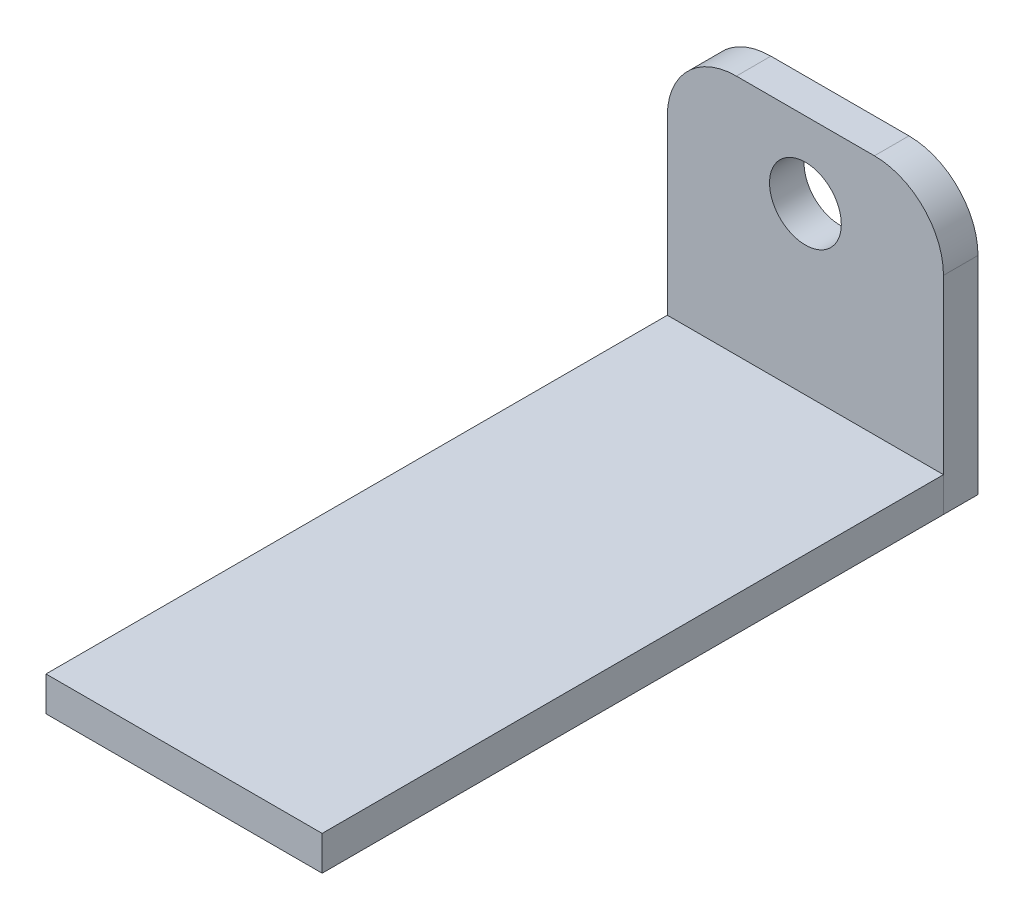
SolidWorks part; units mm, degrees
material "AISI 4130 Steel, annealed at 865C"
ref_plane "Front Plane" through (0, 0, 0) normal (0, 0, 1) x (1, 0, 0)
ref_plane "Top Plane" through (0, 0, 0) normal (0, 1, 0) x (1, 0, 0)
ref_plane "Right Plane" through (0, 0, 0) normal (1, 0, 0) x (0, 0, -1)
sketch "Sketch1" plane through (0, 0, 0) normal (0, 1, 0) x (1, 0, 0)
  line L0 (6.35, 57.15) -> (6.35, 60.325)
  line L1 (0, 0) -> (25.4, 0)
  line L2 (0, 0) -> (0, 57.15)
  line L3 (0, 57.15) -> (25.4, 57.15)
  line L4 (25.4, 0) -> (25.4, 57.15)
  line L5 (0, 0) -> (25.4, 57.15) construction
  line L6 (0, 57.15) -> (25.4, 0) construction
  line L7 (6.35, 60.325) -> (19.05, 60.325)
  line L8 (19.05, 60.325) -> (19.05, 57.15)
  line L9 (18.923, 57.15) -> (18.923, 60.325)
  line L10 (6.477, 57.15) -> (6.477, 60.325)
  point P4 (12.7, 28.575)
  dimension "D1" = 25.4
  dimension "D2" = 57.15
  dimension "D3" = 3.175
  dimension "D4" = 6.35
  dimension "D5" = 6.35
  dimension "D6" = 0.127
  dimension "D7" = 0.127
extrude "Boss-Extrude1" add sketch "Sketch1" along normal blind 3.175 contours L1 L4 L3 L2 | L10 L3 L9 L7
sketch "Sketch2" plane through (0, 0, -57.15) normal (0, 0, -1) x (-1, 0, 0)
  line L0 (-19.05, 0) -> (-19.05, 3.175)
  line L1 (-25.4, 0) -> (0, 0)
  line L2 (-25.4, 0) -> (-25.4, 25.4)
  line L3 (-25.4, 25.4) -> (0, 25.4)
  line L4 (0, 0) -> (0, 25.4)
  line L5 (-25.4, 0) -> (0, 25.4) construction
  line L6 (-25.4, 25.4) -> (0, 0) construction
  line L7 (-18.923, 3.175) -> (-25.4, 3.175) construction
  line L8 (-19.05, 3.175) -> (-6.35, 3.175)
  line L9 (0, 3.175) -> (-6.477, 3.175) construction
  line L10 (-6.35, 3.175) -> (-6.35, 0)
  point P4 (-12.7, 12.7)
  line M2 (0, 0) -> (0, 3.175)
  line M10 (0, 3.175) -> (-6.477, 3.175)
  dimension "D1" = 25.4
  dimension "D2" = 6.35
  dimension "D3" = 6.35
extrude "Boss-Extrude2" add sketch "Sketch2" along normal blind 3.175 separate body contours L0 L8 L4 L3 L2 L1 M10 | L10 L1 M10 M2
sketch "Sketch3" plane through (0, 0, -57.15) normal (0, 0, 1) x (1, 0, 0)
  line L0 (12.7, 3.175) -> (12.7, 18.415) construction
  line L1 (0, 25.4) -> (25.4, 25.4) construction
  line L2 (0, 25.4) -> (0, 3.175) construction
  line L3 (0, 3.175) -> (25.4, 3.175) construction
  line L4 (25.4, 25.4) -> (25.4, 3.175) construction
  line L5 (0, 25.4) -> (25.4, 3.175) construction
  line L6 (0, 3.175) -> (25.4, 25.4) construction
  circle A1 centre (12.7, 18.415) radius 3.302
  dimension "D1" = 6.604
  dimension "D2" = 15.24
extrude "Cut-Extrude1" cut sketch "Sketch3" against normal through all
fillet "Fillet1" radius 6.35 2 edges at (25.4, 25.4, -58.7375) (0, 25.4, -58.7375)
